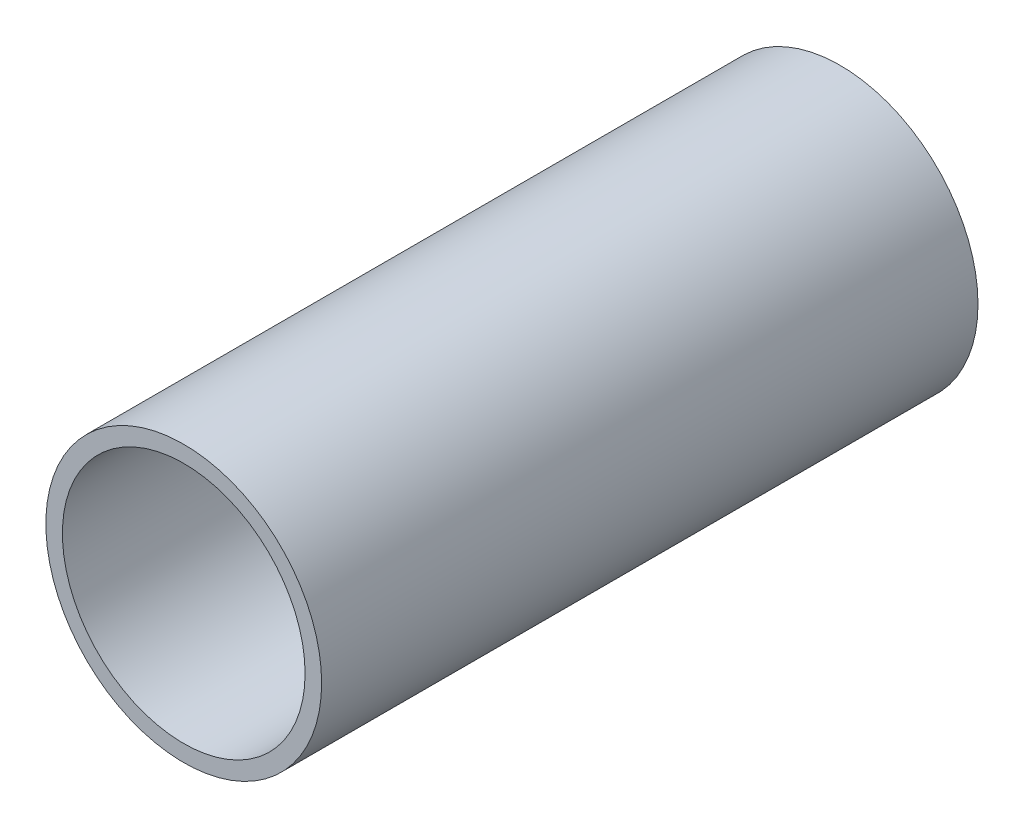
SolidWorks part; units mm, degrees
ref_plane "Front" through (0, 0, 0) normal (0, 0, 1) x (1, 0, 0)
ref_plane "Top" through (0, 0, 0) normal (0, 1, 0) x (1, 0, 0)
ref_plane "Right" through (0, 0, 0) normal (1, 0, 0) x (0, 0, -1)
sketch "Sketch1" plane through (0, 0, 0) normal (0, 0, 1) x (1, 0, 0)
  circle A0 centre (0, 0) radius 6.35
  circle A1 centre (0, 0) radius 5.588
extrude "Boss-Extrude1" add sketch "Sketch1" along normal blind 30.226
